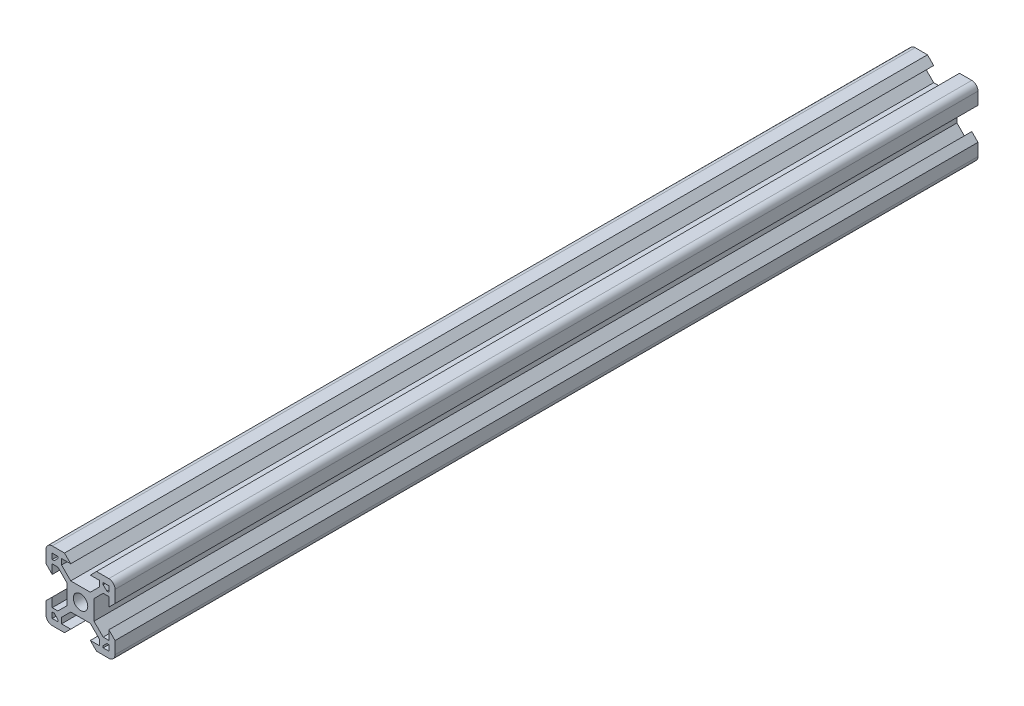
SolidWorks part; units mm, degrees
material "5052-H38, Barre (SS)"
ref_plane "Plan de face" through (0, 0, 0) normal (0, 0, 1) x (1, 0, 0)
ref_plane "Plan de dessus" through (0, 0, 0) normal (0, 1, 0) x (1, 0, 0)
ref_plane "Plan de droite" through (0, 0, 0) normal (1, 0, 0) x (0, 0, -1)
sketch "Esquisse1" plane through (0, 0, 0) normal (0, 0, 1) x (1, 0, 0)
  line L0 (-3.9007, 0) -> (-3.9007, -2.84)
  line L1 (-3.9007, -2.84) -> (-6.56, -5.4993)
  line L2 (-6.56, -5.4993) -> (-8.2, -5.4993)
  line L3 (-8.2, -5.4993) -> (-8.2, -2.84)
  line L4 (-8.2, -2.84) -> (-10, -4.64)
  line L5 (-10, -4.64) -> (-10, -8.2)
  line L6 (0, 0) -> (-17.0509, -17.0509) construction
  line L7 (0, 0) -> (0, -17.0509) construction
  line L8 (0, 0) -> (-30.3777, 0) construction
  line L9 (-4.64, -10) -> (-8.2, -10)
  line L10 (-2.84, -8.2) -> (-4.64, -10)
  line L11 (-5.4993, -8.2) -> (-2.84, -8.2)
  line L12 (-5.4993, -6.56) -> (-5.4993, -8.2)
  line L13 (-2.84, -3.9007) -> (-5.4993, -6.56)
  line L14 (0, -3.9007) -> (-2.84, -3.9007)
  line L15 (-8.2, -8.2) -> (-8.2, -6.5693)
  line L16 (-8.2, -6.5693) -> (-7.63, -6.5693)
  line L17 (-7.63, -6.5693) -> (-6.5693, -7.63)
  line L18 (-6.5693, -7.63) -> (-6.5693, -8.2)
  line L19 (-6.5693, -8.2) -> (-8.2, -8.2)
  line L20 (-3.9007, 0) -> (-3.9007, 2.84)
  line L21 (-3.9007, 2.84) -> (-6.56, 5.4993)
  line L22 (-6.56, 5.4993) -> (-8.2, 5.4993)
  line L23 (-8.2, 5.4993) -> (-8.2, 2.84)
  line L24 (-8.2, 2.84) -> (-10, 4.64)
  line L25 (-10, 4.64) -> (-10, 8.2)
  line L26 (-4.64, 10) -> (-8.2, 10)
  line L27 (-2.84, 8.2) -> (-4.64, 10)
  line L28 (-5.4993, 8.2) -> (-2.84, 8.2)
  line L29 (-5.4993, 6.56) -> (-5.4993, 8.2)
  line L30 (-2.84, 3.9007) -> (-5.4993, 6.56)
  line L31 (0, 3.9007) -> (-2.84, 3.9007)
  line L32 (-8.2, 6.5693) -> (-8.2, 8.2)
  line L33 (-8.2, 8.2) -> (-6.5693, 8.2)
  line L34 (-6.5693, 8.2) -> (-6.5693, 7.63)
  line L35 (-6.5693, 7.63) -> (-7.63, 6.5693)
  line L36 (-7.63, 6.5693) -> (-8.2, 6.5693)
  line L37 (0, 3.9007) -> (2.84, 3.9007)
  line L38 (2.84, 3.9007) -> (5.4993, 6.56)
  line L39 (5.4993, 6.56) -> (5.4993, 8.2)
  line L40 (5.4993, 8.2) -> (2.84, 8.2)
  line L41 (2.84, 8.2) -> (4.64, 10)
  line L42 (4.64, 10) -> (8.2, 10)
  line L43 (10, 4.64) -> (10, 8.2)
  line L44 (8.2, 2.84) -> (10, 4.64)
  line L45 (8.2, 5.4993) -> (8.2, 2.84)
  line L46 (6.56, 5.4993) -> (8.2, 5.4993)
  line L47 (3.9007, 2.84) -> (6.56, 5.4993)
  line L48 (3.9007, 0) -> (3.9007, 2.84)
  line L49 (6.5693, 8.2) -> (8.2, 8.2)
  line L50 (8.2, 8.2) -> (8.2, 6.5693)
  line L51 (8.2, 6.5693) -> (7.63, 6.5693)
  line L52 (7.63, 6.5693) -> (6.5693, 7.63)
  line L53 (6.5693, 7.63) -> (6.5693, 8.2)
  line L54 (3.9007, 0) -> (3.9007, -2.84)
  line L55 (3.9007, -2.84) -> (6.56, -5.4993)
  line L56 (6.56, -5.4993) -> (8.2, -5.4993)
  line L57 (8.2, -5.4993) -> (8.2, -2.84)
  line L58 (8.2, -2.84) -> (10, -4.64)
  line L59 (10, -4.64) -> (10, -8.2)
  line L60 (4.64, -10) -> (8.2, -10)
  line L61 (2.84, -8.2) -> (4.64, -10)
  line L62 (5.4993, -8.2) -> (2.84, -8.2)
  line L63 (5.4993, -6.56) -> (5.4993, -8.2)
  line L64 (2.84, -3.9007) -> (5.4993, -6.56)
  line L65 (0, -3.9007) -> (2.84, -3.9007)
  line L66 (8.2, -6.5693) -> (8.2, -8.2)
  line L67 (8.2, -8.2) -> (6.5693, -8.2)
  line L68 (6.5693, -8.2) -> (6.5693, -7.63)
  line L69 (6.5693, -7.63) -> (7.63, -6.5693)
  line L70 (7.63, -6.5693) -> (8.2, -6.5693)
  circle A0 centre (0, 0) radius 2.1
  arc A1 (-10, -8.2) -> (-8.2, -10) centre (-8.2, -8.2) ccw
  arc A2 (-8.2, 10) -> (-10, 8.2) centre (-8.2, 8.2) ccw
  arc A3 (10, 8.2) -> (8.2, 10) centre (8.2, 8.2) ccw
  arc A4 (8.2, -10) -> (10, -8.2) centre (8.2, -8.2) ccw
  point P23 (-7.0997, -7.0997)
  dimension "D4" = 4.2
  dimension "D1" = 45
  dimension "D2" = 5.68
  dimension "D3" = 1.64
  dimension "D5" = 1.5
  dimension "D6" = 20
  dimension "D7" = 1.8
  dimension "D8" = 1.07
  dimension "D9" = 4
extrude "Boss.-Extru.2" add sketch "Esquisse1" along normal mid plane 250
